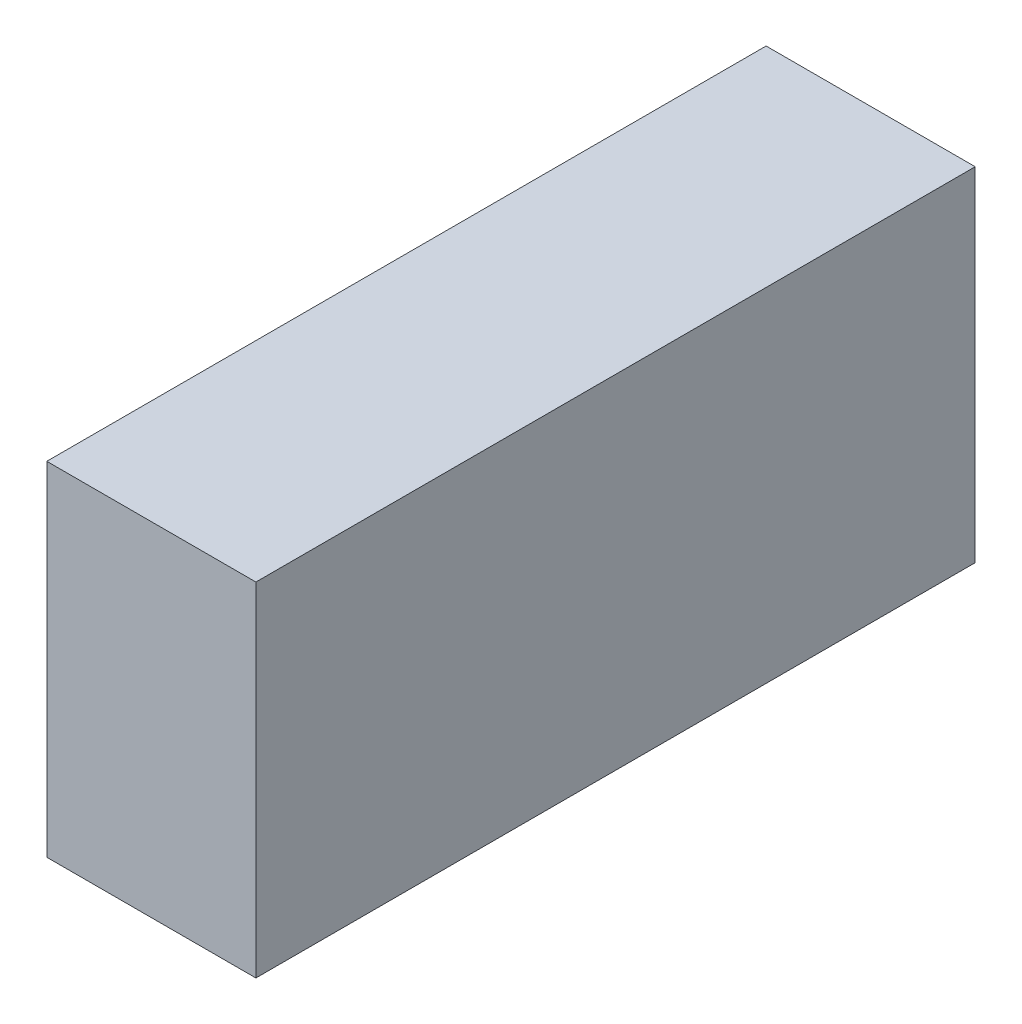
SolidWorks part; units mm, degrees
ref_plane "Front Plane" through (0, 0, 0) normal (0, 0, 1) x (1, 0, 0)
ref_plane "Top Plane" through (0, 0, 0) normal (0, 1, 0) x (1, 0, 0)
ref_plane "Right Plane" through (0, 0, 0) normal (1, 0, 0) x (0, 0, -1)
sketch "Sketch1" plane through (0, 0, 0) normal (0, 0, 1) x (1, 0, 0)
  line L1 (0, 0) -> (12.5, 0)
  line L2 (0, 0) -> (0, 20.5)
  line L3 (0, 20.5) -> (12.5, 20.5)
  line L4 (12.5, 0) -> (12.5, 20.5)
  dimension "D1" = 20.5
  dimension "D2" = 12.5
extrude "Boss-Extrude1" add sketch "Sketch1" along normal blind 43
